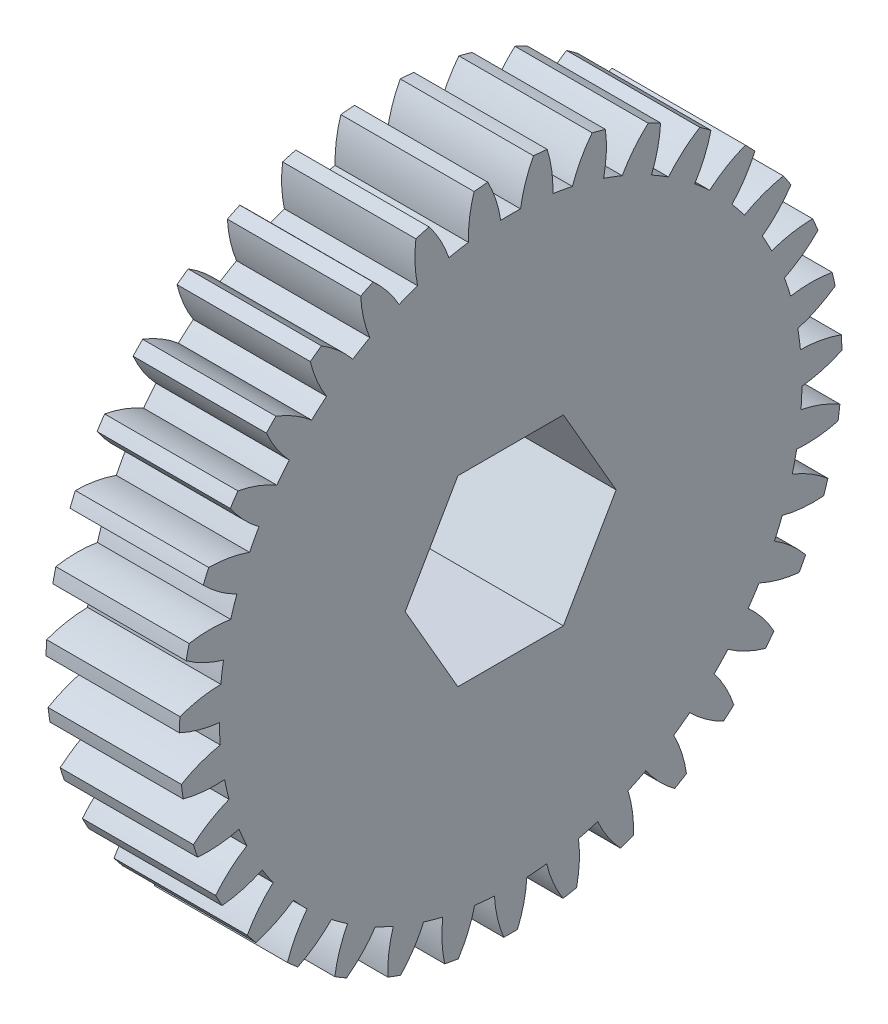
SolidWorks part; units mm, degrees
ref_plane "Plane1" through (0, 0, 0) normal (0, 0, 1) x (1, 0, 0)
ref_plane "Plane2" through (0, 0, 0) normal (0, 1, 0) x (1, 0, 0)
ref_plane "Plane3" through (0, 0, 0) normal (1, 0, 0) x (0, 0, -1)
sketch "HoldingSke" plane through (0, 0, 0) normal (0, 1, 0) x (1, 0, 0)
  line L0 (0, 0) -> (416.1292, -291.3768)
  line L1 (-15, 0) -> (100, 0) construction
  line L2 (0, 0) -> (-2.1039, 2.3779)
  line L3 (0, 0) -> (-11.863, 4.5341)
  line L4 (0, 0) -> (7.0742, 4.9534)
  line L5 (0, 0) -> (-47.5972, -17.7524)
  line L6 (0, 0) -> (-7.8327, -5.2847)
  line L7 (-2.1039, 2.3779) -> (8.8308, 51.9871)
  line L8 (-76.2, 54.61) -> (-75.184, 54.61)
  line L9 (-67.7845, 28.3722) -> (-49.3413, 33.142)
  line L10 (-76.2, 71.12) -> (104.1128, 71.12)
  line L11 (0, 0) -> (-9.4488, 0)
  line L12 (-76.2, 101.6) -> (-76.1492, 101.6)
  line L13 (24.9733, 27.94) -> (52.9518, 28.4284)
  line L14 (24.9733, 27.94) -> (25.0241, 27.9398)
  line L15 (24.9733, 27.94) -> (100.4021, 29.52)
  circle A0 centre (0, 0) radius 0.3969
  circle A1 centre (0, 0) radius 20.6502
  circle A2 centre (0, 0) radius 38.1
  circle A3 centre (0, 0) radius 0.3969
  dimension "MHD" = 41.3004
  dimension "Hub_dia" = 76.2
  dimension "Bore" = 0.7937
  dimension "MBD" = 0.7937
  dimension "Num_teeth" = 35
  dimension "Pitch" = 508
  dimension "Overall_len" = 50.8
  dimension "Show_teeth" = 35
  dimension "Thickness" = 9.4488
  dimension "OAL" = 50.8001
  dimension "T_dim" = 1.016
  dimension "Ap" = 14.5
  dimension "H" = 19.05
  dimension "Pitch_radius" = 180.3128
  dimension "Width" = 9.4488
  dimension "Backlash" = 0.0508
  dimension "Addendum_fac" = 1
  dimension "Dedendum_fac" = 1.2
  dimension "Clearance_fac" = 0.2
  dimension "Dedendum_add" = 0.0508
sketch "BasProSke" plane through (0, 0, 0) normal (0, 1, 0) x (1, 0, 0)
  line L0 (-10, 0) -> (60, 0) construction
  line L1 (0, 0) -> (0, 23.495)
  line L2 (0, 0) -> (9.4488, 0)
  line L3 (9.4488, 0) -> (9.4488, 23.495)
  line L4 (9.4488, 23.495) -> (0, 23.495)
  dimension "Thickness" = 9.4488
  dimension "Diameter" = 46.99
revolve "Base-Revolve" add sketch "BasProSke" angle 360 about L0
sketch "TooCutSke" plane through (0, 0, 0) normal (1, 0, 0) x (0, 0, -1)
  line L1 (0, 0) -> (0, 107) construction
  line L2 (0, 0) -> (-1.086, 22.1985) construction
  line L3 (0, 0) -> (-3.9811, 44.2341) construction
  line L4 (-1.086, 22.1985) -> (-1.9906, 22.117) construction
  arc A0 (0.7034, 20.6382) -> (-0.7034, 20.6382) centre (0, 0) ccw
  arc A1 (1.6338, 23.4636) -> (-1.6338, 23.4636) centre (0, 0) ccw
  circle A2 centre (0, 0) radius 22.225 construction
  circle A3 centre (0, 0) radius 21.5171 construction
  arc A4 (-0.7034, 20.6382) -> (-1.6338, 23.4636) centre (-9.4935, 19.3095) ccw
  arc A5 (1.6338, 23.4636) -> (0.7034, 20.6382) centre (9.4935, 19.3095) ccw
  dimension "Root_dia" = 41.3004
  dimension "Overcut_dia" = 47.0408
  dimension "Pitch_dia" = 44.45
  dimension "Base_dia" = 43.0342
  dimension "Flank_rad" = 8.89
  dimension "Half_ang" = 5.143
  dimension "Half_CT" = 0.9082
extrude "ToothCut" cut sketch "TooCutSke" along normal through all
fillet "Breaks" [suppressed] radius 0.0254
fillet "RootFillets" [suppressed] radius 0.3048
pattern_circular "TeethCuts" count 35 every 10.286 about axis through (-10, 0, 0) along (1, 0, 0) of "ToothCut", "RootFillets", "Breaks"
sketch "HubNeaOneSke" plane through (0, 0, 0) normal (-1, 0, 0) x (0, 0, 1)
  circle A0 centre (0, 0) radius 20.6502
  dimension "Diameter" = 41.3004
extrude "HubNearOne" [suppressed] add sketch "HubNeaOneSke" along normal blind 41.3513
sketch "HubNeaBotSke" plane through (0, 0, 0) normal (-1, 0, 0) x (0, 0, 1)
  circle A0 centre (0, 0) radius 20.6502
  dimension "Diameter" = 41.3004
extrude "HubNearBoth" [suppressed] add sketch "HubNeaBotSke" along normal blind 20.6756
ref_plane "FarPln" through (9.4488, 0, 0) normal (1, 0, 0) x (0, 0, -1)
sketch "HubFarSke" plane through (9.4488, 0, 0) normal (1, 0, 0) x (0, 0, -1)
  circle A0 centre (0, 0) radius 20.6502
  dimension "Diameter" = 41.3004
extrude "HubFar" [suppressed] add sketch "HubFarSke" along normal blind 20.6756
sketch "BorSke" plane through (0, 0, 0) normal (1, 0, 0) x (0, 0, -1)
  circle A0 centre (0, 0) radius 0.3969
  dimension "Diameter" = 0.7937
extrude "Bore" cut sketch "BorSke" along normal mid plane 101.6001
sketch "KeySke" plane through (0, 0, 0) normal (1, 0, 0) x (0, 0, -1)
  line L0 (-0.127, 0) -> (-0.127, 0.6191)
  line L1 (-0.127, 0.6191) -> (0.127, 0.6191)
  line L2 (0.127, 0.6191) -> (0.127, 0)
  line L3 (0, 0) -> (0, 34) construction
  line L4 (-0.127, 0) -> (0.127, 0)
  dimension "Offset" = 0.6191
  dimension "Width" = 0.254
extrude "Keyway" [suppressed] cut sketch "KeySke" along normal mid plane 101.6001
pattern_circular "Keyway2" [suppressed] count 2 every 90 about axis through (-10, 0, 0) along (1, 0, 0)
sketch "Sketch2" plane through (0, 0, 0) normal (-1, 0, 0) x (0, 0, 1)
  line L1 (7.479, 0) -> (3.7395, 6.477)
  line L2 (3.7395, 6.477) -> (-3.7395, 6.477)
  line L3 (-3.7395, 6.477) -> (-7.479, 0)
  line L4 (-7.479, 0) -> (-3.7395, -6.477)
  line L5 (-3.7395, -6.477) -> (3.7395, -6.477)
  line L6 (3.7395, -6.477) -> (7.479, 0)
  circle A0 centre (0, 0) radius 6.477 construction
  dimension "D1" = 12.954
sketch "Sketch4" plane through (0, 0, 0) normal (-1, 0, 0) x (0, 0, 1)
  circle A0 centre (0, 0) radius 9.525
  dimension "D1" = 19.05
extrude "Boss-Extrude2" add sketch "Sketch4" along normal blind 1.5875
extrude "Cut-Extrude3" cut sketch "Sketch2" against normal through all both and the other way through all
equation "' \"Pitch@HoldingSke\" = 4"
equation "' \"Num_teeth@HoldingSke\" = 12"
equation "' \"Ap@HoldingSke\" =  20"
equation "' \"Ap@HoldingSke\" = 20"
equation "' \"Width@HoldingSke\" = 0.5"
equation "' \"Hub_dia@HoldingSke\"= 1"
equation "' \"Hub_dia@HoldingSke\" = 1"
equation "' \"Overall_len@HoldingSke\" = 1.0"
equation "' \"Bore@HoldingSke\" = 0.75"
equation "' \"T_dim@HoldingSke\" = 0.85"
equation "' \"Width@KeySke\" = 0.25"
equation "' \"Show_teeth@HoldingSke\" = 13"
equation "' \"Backlash@HoldingSke\" = 0.009"
equation "' \"Addendum_fac@HoldingSke\" = 1.0"
equation "' \"Dedendum_fac@HoldingSke\" = 1.25"
equation "' \"Dedendum_add@HoldingSke\" = 0.00005"
equation "' \"Clearance_fac@HoldingSke\" = 0.25"
equation "' \"Pitch@HoldingSke\" = 0.5"
equation "' \"Num_teeth@HoldingSke\" = 23"
equation "' \"Show_teeth@HoldingSke\" = 23"
equation "' \"Backlash@HoldingSke\" = 0.0375"
equation "\"Overcut_dia@TooCutSke\" = (\"Num_teeth@HoldingSke\" + 2 * \"Addendum_fac@HoldingSke\") / \"Pitch@HoldingSke\" + 0.002"
equation "\"Pitch_dia@TooCutSke\" = \"Num_teeth@HoldingSke\" / \"Pitch@HoldingSke\""
equation "\"Base_dia@TooCutSke\" = \"Num_teeth@HoldingSke\" / \"Pitch@HoldingSke\" * cos((\"Ap@HoldingSke\"  * 3.14159265 / 180))"
equation "\"Root_dia@TooCutSke\" = (\"Num_teeth@HoldingSke\" + 2) / \"Pitch@HoldingSke\" - 2 * (\"Addendum_fac@HoldingSke\" + \"Dedendum_fac@HoldingSke\") / \"Pitch@HoldingSke\" - \"Dedendum_add@HoldingSke\" * 2"
equation "\"Half_ang@TooCutSke\" = 180 / \"Num_teeth@HoldingSke\""
equation "\"Half_CT@TooCutSke\" = \"Num_teeth@HoldingSke\" / \"Pitch@HoldingSke\" * sin((3.14159265 / 2 / \"Num_teeth@HoldingSke\")) / 2 - 7 * \"Backlash@HoldingSke\" / 4"
equation "\"Flank_rad@TooCutSke\" = \"Num_teeth@HoldingSke\" / \"Pitch@HoldingSke\" / 5"
equation "\"Radius@RootFillets\" = \"Clearance_fac@HoldingSke\" / \"Pitch@HoldingSke\" + \"Dedendum_add@HoldingSke\""
equation "\"Break_rad@Breaks\" = 0.02 / \"Pitch@HoldingSke\""
equation "\"Thickness@HoldingSke\" = \"Width@HoldingSke\""
equation "\"OAL@HoldingSke\" = \"Thickness@HoldingSke\""
equation "\"MHD@HoldingSke\" = (\"Num_teeth@HoldingSke\" + 2) / \"Pitch@HoldingSke\" - 2 * (\"Addendum_fac@HoldingSke\" + \"Dedendum_fac@HoldingSke\")  / \"Pitch@HoldingSke\" - \"Dedendum_add@HoldingSke\" * 2"
equation "\"MBD@HoldingSke\" = (\"Num_teeth@HoldingSke\" + 2) / \"Pitch@HoldingSke\" - 2 * (\"Addendum_fac@HoldingSke\" + \"Dedendum_fac@HoldingSke\")  / \"Pitch@HoldingSke\" - \"Dedendum_add@HoldingSke\" * 2 - 0.002"
equation "\"MHD@HoldingSke\" = ((sgn( \"MHD@HoldingSke\" - \"Hub_dia@HoldingSke\" )-1)*( \"MHD@HoldingSke\" - \"Hub_dia@HoldingSke\" ))/-2+ \"Hub_dia@HoldingSke\""
equation "\"MBD@HoldingSke\" = ((sgn( \"MBD@HoldingSke\" - \"Bore@HoldingSke\" )-1)*( \"MBD@HoldingSke\" - \"Bore@HoldingSke\" ))/-2+ \"Bore@HoldingSke\""
equation "\"OAL@HoldingSke\" = ((sgn( \"OAL@HoldingSke\" - \"Overall_len@HoldingSke\" )+1)*( \"OAL@HoldingSke\" - \"Overall_len@HoldingSke\" ))/2 + \"Overall_len@HoldingSke\" + 0.000002"
equation "\"Num_teeth@TeethCuts\" = int( \"Show_teeth@HoldingSke\" ) + 1"
equation "\"Num_teeth@TeethCuts\" = ((sgn( \"Num_teeth@TeethCuts\" - \"Num_teeth@HoldingSke\" )-1)*( \"Num_teeth@TeethCuts\" - \"Num_teeth@HoldingSke\" ))/-2+ \"Num_teeth@HoldingSke\""
equation "\"Num_teeth@TeethCuts\" = ((sgn( \"Num_teeth@TeethCuts\" - 2.0)+1)*( \"Num_teeth@TeethCuts\" - 2.0))/2 +2.0"
equation "\"Angle@TeethCuts\" = 360.0 / \"Num_teeth@HoldingSke\""
equation "\"Diameter@BasProSke\" = (\"Num_teeth@HoldingSke\" + 2 * \"Addendum_fac@HoldingSke\") / \"Pitch@HoldingSke\""
equation "\"Thickness@BasProSke\"  = \"Thickness@HoldingSke\""
equation "' \"Fillet_rad@BasProSke\" =  \"Thickness@HoldingSke\" * 0.05"
equation "' \"Fillet_rad@BasProSke\" = \"Thickness@HoldingSke\" * 0.05"
equation "\"MHD@HoldingSke\" = ((sgn( \"MHD@HoldingSke\" - \"Root_dia@TooCutSke\" )-1)*( \"MHD@HoldingSke\" - \"Root_dia@TooCutSke\" ))/-2+ \"Root_dia@TooCutSke\""
equation "\"Diameter@HubNeaOneSke\" = \"MHD@HoldingSke\""
equation "\"Length@HubNearOne\" = \"OAL@HoldingSke\" - \"Thickness@BasProSke\""
equation "\"Diameter@HubNeaBotSke\" = \"MHD@HoldingSke\""
equation "\"Length@HubNearBoth\" = ( \"OAL@HoldingSke\" - \"Thickness@BasProSke\" ) / 2.0"
equation "\"Thickness@FarPln\" = \"Thickness@BasProSke\""
equation "\"Diameter@HubFarSke\" = \"MHD@HoldingSke\""
equation "\"Length@HubFar\" = ( \"OAL@HoldingSke\" - \"Thickness@BasProSke\" ) / 2.0"
equation "\"Diameter@BorSke\" = \"MBD@HoldingSke\""
equation "\"D1@Bore\" = \"OAL@HoldingSke\" * 2.0"
equation "\"D1@Keyway\" = \"OAL@HoldingSke\" * 2.0"
equation "\"Offset@KeySke\" = \"T_dim@HoldingSke\" - \"MBD@HoldingSke\" / 2.0"
